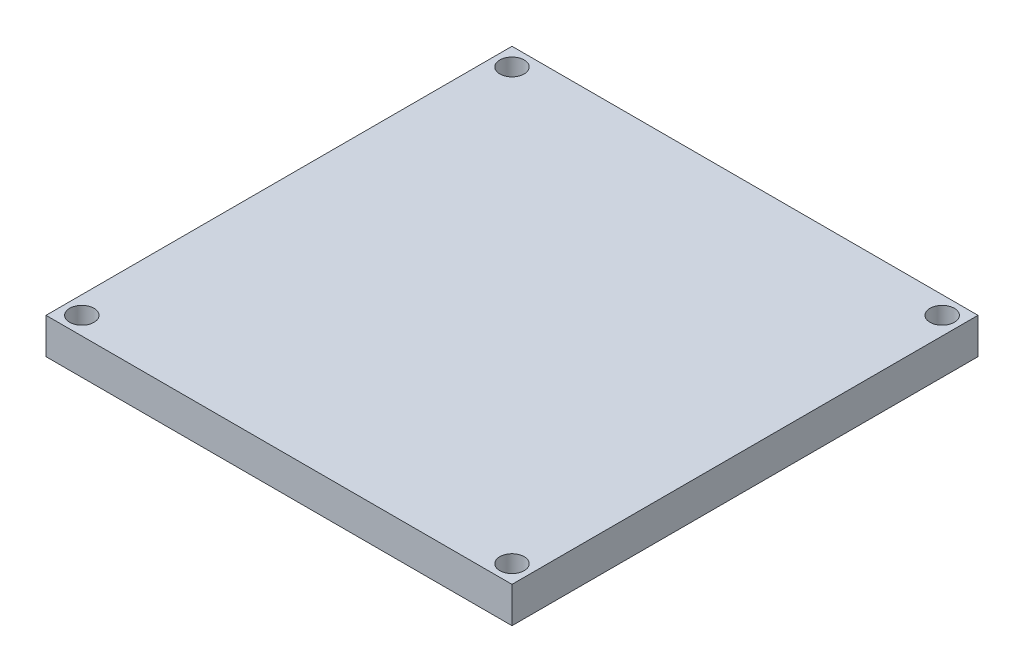
SolidWorks part; units mm, degrees
ref_plane "Front Plane" through (0, 0, 0) normal (0, 0, 1) x (1, 0, 0)
ref_plane "Top Plane" through (0, 0, 0) normal (0, 1, 0) x (1, 0, 0)
ref_plane "Right Plane" through (0, 0, 0) normal (1, 0, 0) x (0, 0, -1)
sketch "Sketch1" plane through (0, 0, 0) normal (0, 1, 0) x (1, 0, 0)
  line L0 (32.5, 65) -> (32.5, 0) construction
  line L1 (0, 0) -> (65, 0)
  line L2 (0, 0) -> (0, 65)
  line L3 (0, 65) -> (65, 65)
  line L4 (65, 0) -> (65, 65)
  line L5 (0, 32.5) -> (65, 32.5) construction
  circle A0 centre (62.5, 62.5) radius 1.7
  circle A2 centre (2.5, 62.5) radius 1.7
  circle A3 centre (62.5, 2.5) radius 1.7
  circle A4 centre (2.5, 2.5) radius 1.7
  dimension "D5" = 3.4
  dimension "D1" = 65
  dimension "D2" = 65
  dimension "D3" = 2.5
  dimension "D4" = 2.5
extrude "Plate" add sketch "Sketch1" along normal blind 5
equation "\"WallSep\" = ( 65 - 60 ) / 2"
equation "\"D4@Sketch1\"=\"WallSep\""
equation "\"D3@Sketch1\"=\"WallSep\""
